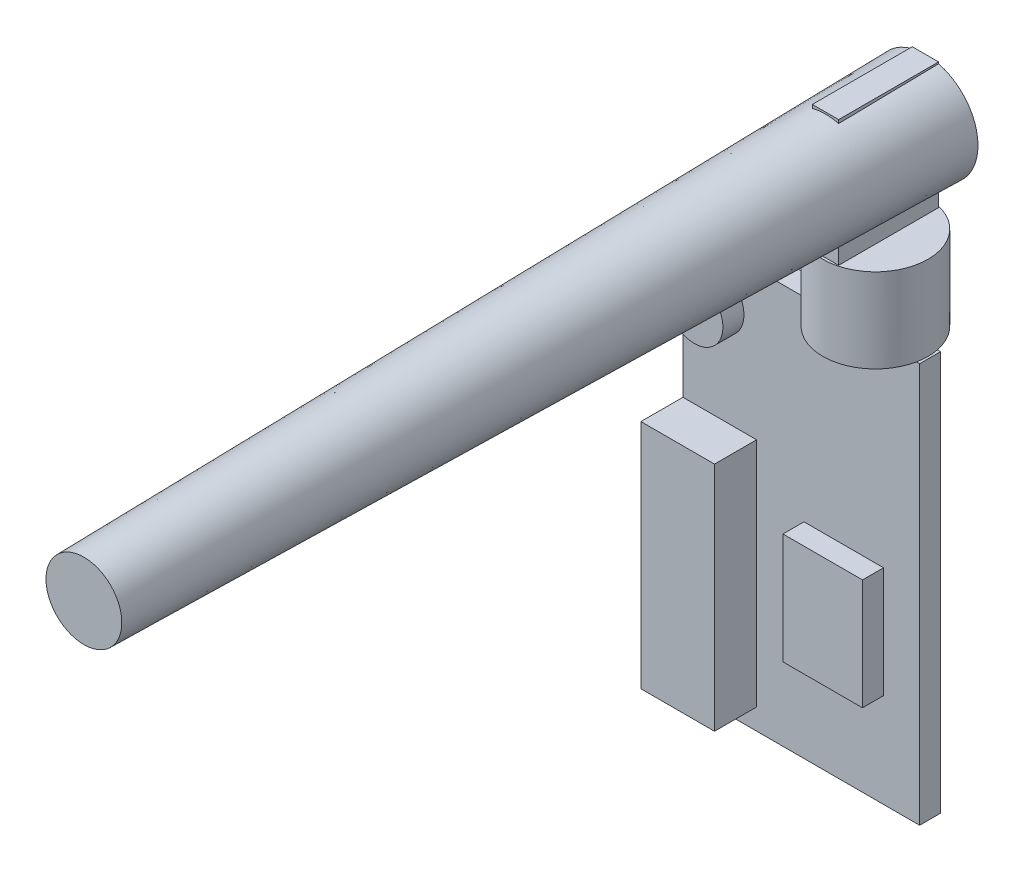
SolidWorks part; units mm, degrees
ref_plane "Front Plane" through (0, 0, 0) normal (0, 0, 1) x (1, 0, 0)
ref_plane "Top Plane" through (0, 0, 0) normal (0, 1, 0) x (1, 0, 0)
ref_plane "Right Plane" through (0, 0, 0) normal (1, 0, 0) x (0, 0, -1)
sketch "Sketch1" plane through (0, 0, 0) normal (0, 0, 1) x (1, 0, 0)
  line L1 (-11.25, -19) -> (11.25, -19)
  line L2 (-11.25, -19) -> (-11.25, 19)
  line L3 (-11.25, 19) -> (11.25, 19)
  line L4 (11.25, -19) -> (11.25, 19)
  line L5 (-11.25, -19) -> (11.25, 19) construction
  line L6 (-11.25, 19) -> (11.25, -19) construction
  point P0 (0, 0)
  dimension "D1" = 38
  dimension "D2" = 22.5
extrude "Boss-Extrude1" add sketch "Sketch1" along normal blind 2
sketch "Sketch2" plane through (0, 0, 2) normal (0, 0, 1) x (1, 0, 0)
  line L0 (-11.25, 19) -> (-11.25, -19) construction
  line L1 (-11.25, -17.0111) -> (-4.25, -17.0111)
  line L2 (-11.25, -17.0111) -> (-11.25, 4.9889)
  line L3 (-11.25, 4.9889) -> (-4.25, 4.9889)
  line L4 (-4.25, -17.0111) -> (-4.25, 4.9889)
  dimension "D1" = 22
  dimension "D2" = 7
extrude "Boss-Extrude2" add sketch "Sketch2" along normal blind 4
sketch "Sketch3" plane through (0, 0, 2) normal (0, 0, 1) x (1, 0, 0)
  line L1 (0.2535, -10.0436) -> (7.8168, -10.0436)
  line L2 (0.2535, -10.0436) -> (0.2535, 0.4861)
  line L3 (0.2535, 0.4861) -> (7.8168, 0.4861)
  line L4 (7.8168, -10.0436) -> (7.8168, 0.4861)
  line L5 (0.2535, -10.0436) -> (7.8168, 0.4861) construction
  line L6 (0.2535, 0.4861) -> (7.8168, -10.0436) construction
  circle A0 centre (-8.1582, 14.6633) radius 2.7062
  point P2 (4.0352, -4.7788)
extrude "Boss-Extrude3" add sketch "Sketch3" along normal blind 2
sketch "Sketch4" plane through (-11.25, 0, 0) normal (-1, 0, 0) x (0, 0, 1)
  line L1 (1.479, -15.41) -> (5.0013, -15.41)
  line L2 (1.479, -15.41) -> (1.479, 3.4823)
  line L3 (1.479, 3.4823) -> (5.0013, 3.4823)
  line L4 (5.0013, -15.41) -> (5.0013, 3.4823)
  line L5 (1.479, -15.41) -> (5.0013, 3.4823) construction
  line L6 (1.479, 3.4823) -> (5.0013, -15.41) construction
  point P0 (3.2402, -5.9639)
extrude "Cut-Extrude1" cut sketch "Sketch4" against normal blind 6
sketch "Sketch5" plane through (0, 19, 0) normal (0, 1, 0) x (1, 0, 0)
  line L0 (-11.25, -1) -> (11.25, -1) construction
  line L1 (-11.25, -2) -> (-11.25, 0) construction
  line L2 (11.25, -2) -> (11.25, 0) construction
  circle A0 centre (6.05, -1) radius 5
  dimension "D1" = 10
  dimension "D2" = 5.2
extrude "Boss-Extrude4" add sketch "Sketch5" along normal blind 20
sketch "Sketch6" plane through (0, 39, 0) normal (0, 1, 0) x (1, 0, 0)
  line L1 (4.8, -5.75) -> (7.3, -5.75)
  line L2 (4.8, -5.75) -> (4.8, 3.75)
  line L3 (4.8, 3.75) -> (7.3, 3.75)
  line L4 (7.3, -5.75) -> (7.3, 3.75)
  line L5 (4.8, -5.75) -> (7.3, 3.75) construction
  line L6 (4.8, 3.75) -> (7.3, -5.75) construction
  point P0 (6.05, -1)
  dimension "D1" = 2.5
  dimension "D2" = 9.5
extrude "Cut-Extrude2" cut sketch "Sketch6" against normal blind 12 flip side to cut
sketch "Sketch7" plane through (0, 0, -3.75) normal (0, 0, -1) x (-1, 0, 0)
  line L0 (-6.05, 39) -> (-6.05, 27) construction
  line L1 (-7.3, 39) -> (-4.8, 39) construction
  line L2 (-7.3, 27) -> (-4.8, 27) construction
  circle A0 centre (-6.05, 34) radius 5
  dimension "D1" = 10
extrude "Boss-Extrude5" add sketch "Sketch7" against normal blind 80 draft 1
